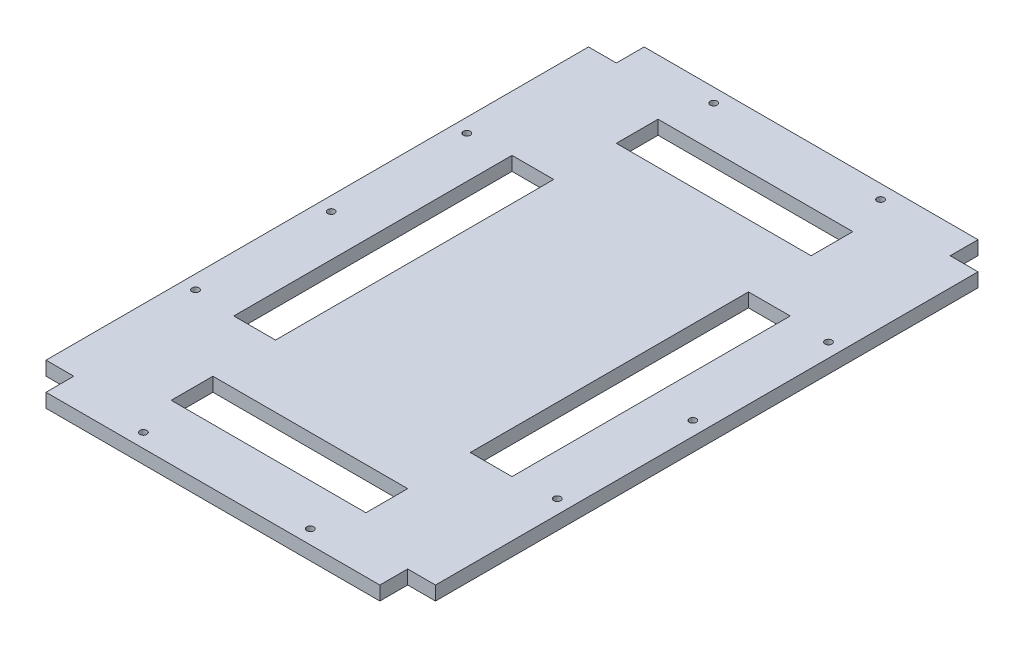
SolidWorks part; units mm, degrees
material "Maple"
ref_plane "Front Plane" through (0, 0, 0) normal (0, 0, 1) x (1, 0, 0)
ref_plane "Top Plane" through (0, 0, 0) normal (0, 1, 0) x (1, 0, 0)
ref_plane "Right Plane" through (0, 0, 0) normal (1, 0, 0) x (0, 0, -1)
sketch "Sketch1" plane through (0, 0, 0) normal (0, 1, 0) x (1, 0, 0)
  line L0 (-140, 215) -> (-120, 215)
  line L1 (-140, 215) -> (140, 215)
  line L2 (-140, 215) -> (-140, -215)
  line L3 (-140, -215) -> (140, -215)
  line L4 (140, 215) -> (140, -215)
  line L5 (-140, 215) -> (140, -215) construction
  line L6 (-140, -215) -> (140, 215) construction
  line L7 (-120, 215) -> (-120, 195)
  line L8 (-120, 195) -> (-140, 195)
  line L9 (-140, 195) -> (-140, 215)
  line L10 (0, 0) -> (0, 215) construction
  line L11 (140, 195) -> (140, 215)
  line L12 (120, 195) -> (140, 195)
  line L13 (120, 215) -> (120, 195)
  line L14 (140, 215) -> (120, 215)
  line L15 (0, 0) -> (-140, 0) construction
  line L16 (140, -195) -> (140, -215)
  line L17 (120, -195) -> (140, -195)
  line L18 (120, -215) -> (120, -195)
  line L19 (140, -215) -> (120, -215)
  line L20 (-140, -195) -> (-140, -215)
  line L21 (-120, -195) -> (-140, -195)
  line L22 (-120, -215) -> (-120, -195)
  line L23 (-140, -215) -> (-120, -215)
  point P0 (0, 0)
  dimension "D1" = 280
  dimension "D2" = 430
  dimension "D3" = 20
  dimension "D4" = 20
extrude "Boss-Extrude1" add sketch "Sketch1" along normal mid plane 10 contours L22 L3 L18 L17 L4 L12 L13 L1 L7 L8 L2 L21
sketch "Sketch2" plane through (0, 5, 0) normal (0, 1, 0) x (1, 0, 0)
  line L0 (70, 100) -> (100, 100)
  line L5 (70, 100) -> (70, -100)
  line L6 (70, -100) -> (100, -100)
  line L7 (100, 100) -> (100, -100)
  line L9 (140, 195) -> (140, -195) construction
  line L10 (-100, 100) -> (-70, 100)
  line L11 (-100, 100) -> (-100, -100)
  line L12 (-100, -100) -> (-70, -100)
  line L13 (-70, 100) -> (-70, -100)
  line L14 (-140, 195) -> (-140, -195) construction
  line L15 (-120, -215) -> (120, -215) construction
  line L16 (-70, 175) -> (70, 175)
  line L17 (-70, 175) -> (-70, 145)
  line L18 (-70, 145) -> (70, 145)
  line L19 (70, 175) -> (70, 145)
  line L20 (-70, -145) -> (70, -145)
  line L21 (-70, -145) -> (-70, -175)
  line L22 (-70, -175) -> (70, -175)
  line L23 (70, -145) -> (70, -175)
  line L24 (-120, 215) -> (120, 215) construction
  line L25 (-120, 215) -> (-120, 195) construction
  circle A0 centre (-60, 205) radius 2.5
  circle A1 centre (60, 205) radius 2.5
  circle A2 centre (130, 97.5) radius 2.5
  circle A3 centre (130, -97.5) radius 2.5
  circle A4 centre (130, 0) radius 2.5
  circle A5 centre (60, -205) radius 2.5
  circle A6 centre (-60, -205) radius 2.5
  circle A7 centre (-130, 97.5) radius 2.5
  circle A8 centre (-130, 0) radius 2.5
  circle A9 centre (-130, -97.5) radius 2.5
  point P11 (-70, 0)
  point P12 (70, 0)
  point P25 (0, 145)
  point P26 (0, -145)
  point P50 (0, 0)
  point P51 (0, 0)
  point P52 (0, 0)
  point P53 (0, 0)
  point P54 (0, 0)
  point P55 (0, 0)
  point P56 (0, 0)
  point P57 (0, 0)
  point P58 (0, 0)
  point P61 (0, 0)
  dimension "D21" = 5
  dimension "D1" = 200
  dimension "D2" = 30
  dimension "D3" = 200
  dimension "D4" = 30
  dimension "D5" = 40
  dimension "D6" = 40
  dimension "D7" = 140
  dimension "D8" = 140
  dimension "D9" = 30
  dimension "D10" = 30
  dimension "D11" = 40
  dimension "D12" = 40
  dimension "D13" = 10
  dimension "D14" = 10
  dimension "D15" = 10
  dimension "D16" = 10
  dimension "D17" = 120
  dimension "D18" = 60
  dimension "D19" = 195
  dimension "D20" = 97.5
extrude "Cut-Extrude1" cut sketch "Sketch2" against normal blind 10
